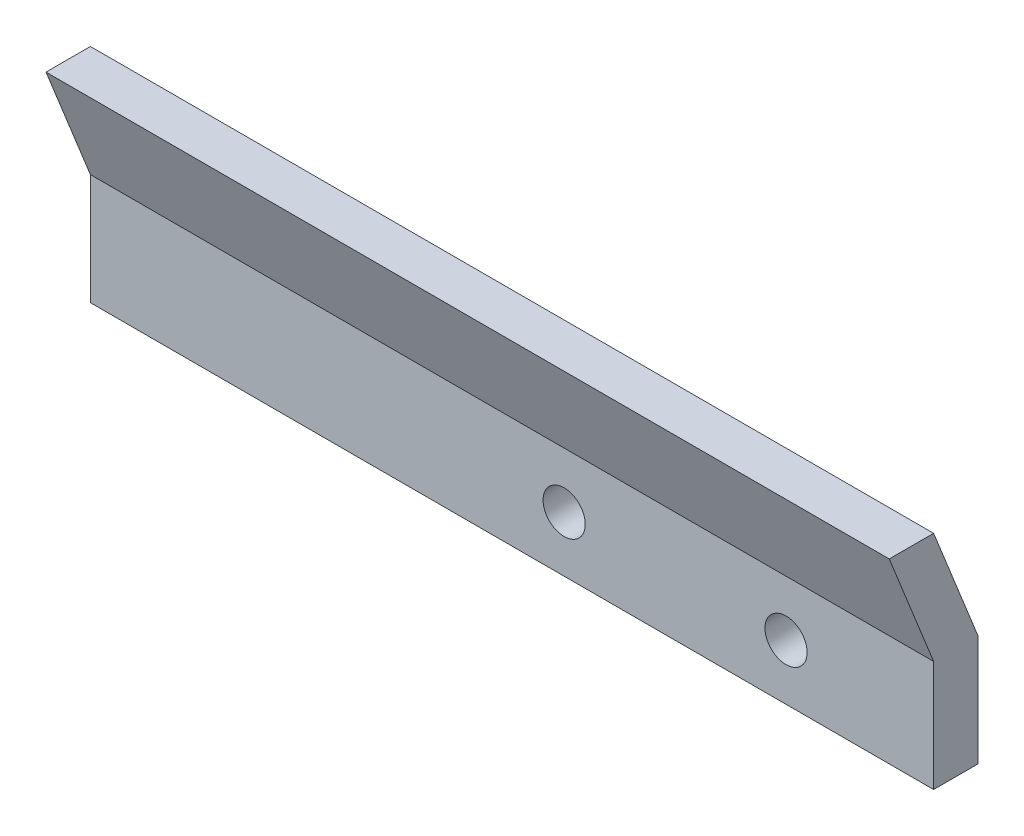
SolidWorks part; units mm, degrees
ref_plane "前视基准面" through (0, 0, 0) normal (0, 0, 1) x (1, 0, 0)
ref_plane "上视基准面" through (0, 0, 0) normal (0, 1, 0) x (1, 0, 0)
ref_plane "右视基准面" through (0, 0, 0) normal (1, 0, 0) x (0, 0, -1)
other "Configuration Table"
sketch "草图1" plane through (0, 0, 0) normal (0, 0, 1) x (1, 0, 0)
  line L1 (0, 0) -> (38, 0)
  line L2 (0, 0) -> (0, -5)
  line L3 (0, -5) -> (38, -5)
  line L4 (38, 0) -> (38, -5)
  circle A0 centre (31.35, -2.5) radius 0.95
  dimension "D3" = 1.9
  dimension "D1" = 5
  dimension "D2" = 38
  dimension "D4" = 31.35
  dimension "D5" = 2.5
extrude "凸台-拉伸1" add sketch "草图1" along normal blind 2
sketch "草图2" plane through (38, 0, 0) normal (1, 0, 0) x (0, 0, -1)
  line L0 (0, 0) -> (-2, 5)
  line L1 (-2, 5) -> (-4, 5)
  line L2 (-4, 5) -> (-2, 0)
  line L3 (-2, 0) -> (0, 0)
  dimension "D1" = 5
  dimension "D2" = 2
extrude "凸台-拉伸2" add sketch "草图2" against normal blind 38
sketch "草图3" plane through (0, 0, 2) normal (0, 0, 1) x (1, 0, 0)
  circle A0 centre (21.35, -2.5) radius 0.95
  circle A2 centre (31.35, -2.5) radius 0.95 construction
  dimension "D1" = 1.9
  dimension "D2" = 10
extrude "切除-拉伸1" cut sketch "草图3" against normal blind 12
